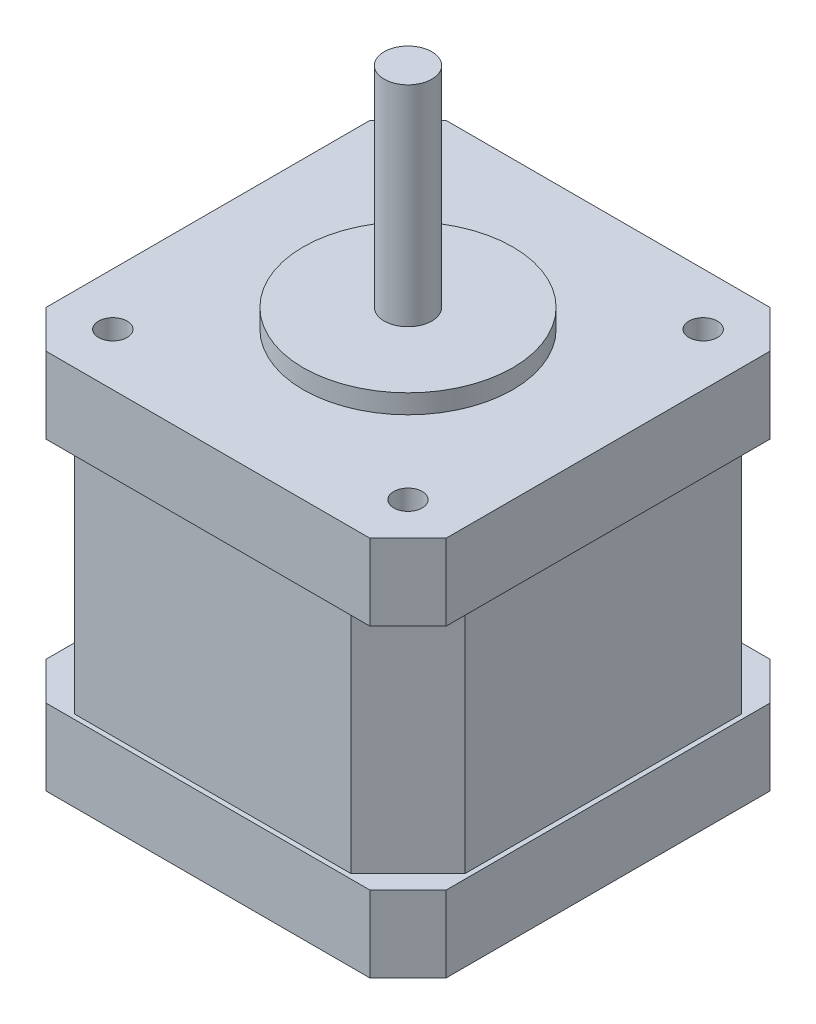
SolidWorks part; units mm, degrees
ref_plane "Front Plane" through (0, 0, 0) normal (0, 0, 1) x (1, 0, 0)
ref_plane "Top Plane" through (0, 0, 0) normal (0, 1, 0) x (1, 0, 0)
ref_plane "Right Plane" through (0, 0, 0) normal (1, 0, 0) x (0, 0, -1)
sketch "Sketch1" plane through (0, 0, 0) normal (0, 1, 0) x (1, 0, 0)
  line L0 (-21, 21) -> (21, -21) construction
  line L1 (-21, 21) -> (21, 21)
  line L2 (-21, 21) -> (-21, -21)
  line L3 (-21, -21) -> (21, -21)
  line L4 (21, 21) -> (21, -21)
  dimension "D1" = 42
extrude "Boss-Extrude1" add sketch "Sketch1" along normal blind 8
pattern_linear "LPattern2" count 2 spacing 32 along (0, -1, 0) of bodies 101
sketch "Sketch5" plane through (0, 0, 0) normal (0, -1, 0) x (1, 0, 0)
  line L8 (-20.5, 20.5) -> (-20.5, -20.5)
  line L9 (-20.5, -20.5) -> (20.5, -20.5)
  line L10 (20.5, -20.5) -> (20.5, 20.5)
  line L11 (20.5, 20.5) -> (-20.5, 20.5)
  line L12 (-20.5, 20.5) -> (-20.5, -20.5)
  line L13 (-20.5, -20.5) -> (20.5, -20.5)
  line L14 (20.5, -20.5) -> (20.5, 20.5)
  line L15 (20.5, 20.5) -> (-20.5, 20.5)
  dimension "D1" = 0.5
extrude "Boss-Extrude4" add sketch "Sketch5" along normal up to next
chamfer "Chamfer2" distance 6 angle 45 4 edges at (20.5, -12, -20.5) (20.5, -12, 20.5) (-20.5, -12, 20.5) (-20.5, -12, -20.5)
chamfer "Chamfer1" distance 4 angle 45 8 edges at (-21, 4, -21) (-21, 4, 21) (21, 4, -21) (21, 4, 21) (-21, -28, -21) (-21, -28, 21) (21, -28, -21) (21, -28, 21)
sketch "Sketch2" plane through (0, 8, 0) normal (0, 1, 0) x (1, 0, 0)
  circle A0 centre (0, 0) radius 11
  dimension "D1" = 22
extrude "Boss-Extrude2" add sketch "Sketch2" along normal blind 2
sketch "Sketch3" plane through (0, 10, 0) normal (0, 1, 0) x (1, 0, 0)
  circle A0 centre (0, 0) radius 2.5
  dimension "D1" = 5
extrude "Boss-Extrude3" add sketch "Sketch3" along normal blind 22
sketch "Sketch6" plane through (0, 8, 0) normal (0, 1, 0) x (1, 0, 0)
  line L0 (-15.5, 15.5) -> (15.5, 15.5) construction
  line L1 (15.5, 15.5) -> (15.5, -15.5) construction
  line L2 (15.5, -15.5) -> (-15.5, -15.5) construction
  line L3 (-15.5, -15.5) -> (-15.5, 15.5) construction
  line L4 (-15.5, 15.5) -> (15.5, -15.5) construction
  circle A0 centre (-15.5, 15.5) radius 1.5
  circle A1 centre (15.5, 15.5) radius 1.5
  circle A2 centre (15.5, -15.5) radius 1.5
  circle A3 centre (-15.5, -15.5) radius 1.5
  dimension "D1" = 3
  dimension "D2" = 31
extrude "Cut-Extrude1" cut sketch "Sketch6" against normal blind 7
